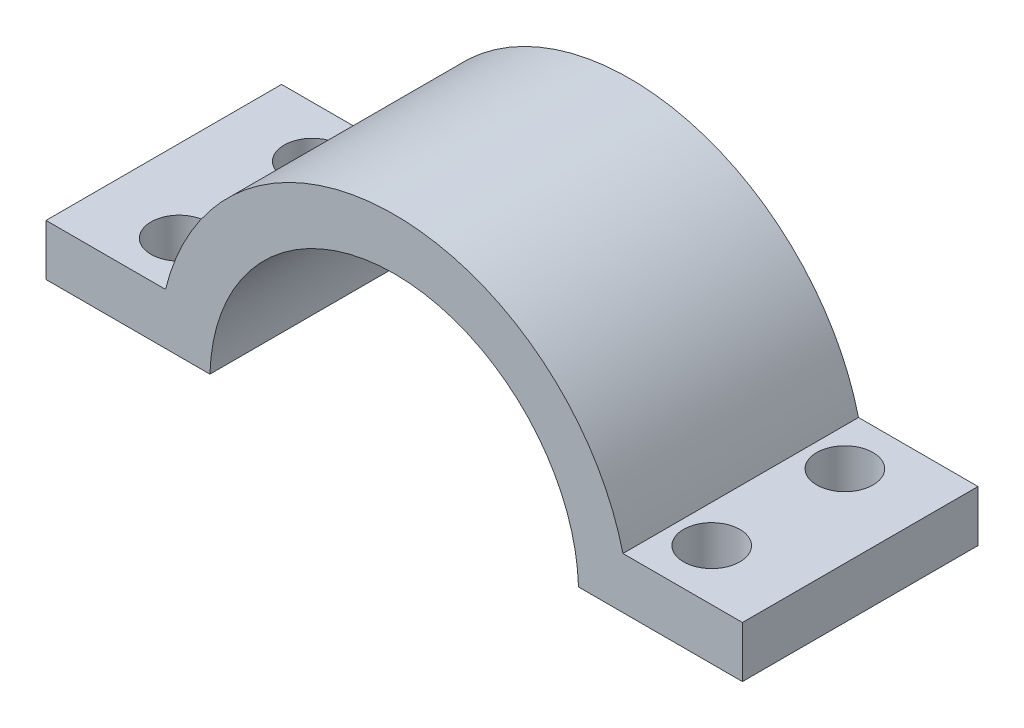
SolidWorks part; units mm, degrees
ref_plane "Front Plane" through (0, 0, 0) normal (0, 0, 1) x (1, 0, 0)
ref_plane "Top Plane" through (0, 0, 0) normal (0, 1, 0) x (1, 0, 0)
ref_plane "Right Plane" through (0, 0, 0) normal (1, 0, 0) x (0, 0, -1)
sketch "Sketch1" plane through (0, 0, 0) normal (0, 0, 1) x (1, 0, 0)
  line L0 (-17.9931, 0.5) -> (-34, 0.5)
  line L1 (-34, 0.5) -> (-34, 5.5)
  line L2 (-34, 5.5) -> (-22.3327, 5.5)
  line L3 (17.9931, 0.5) -> (34, 0.5)
  line L4 (34, 0.5) -> (34, 5.5)
  line L5 (34, 5.5) -> (22.3327, 5.5)
  arc A0 (17.9931, 0.5) -> (-17.9931, 0.5) centre (0, 0) ccw
  arc A1 (22.3327, 5.5) -> (-22.3327, 5.5) centre (0, 0) ccw
  circle A2 centre (0, 0) radius 23 construction
  circle A3 centre (0, 0) radius 18 construction
  point P4 (21.972, 1.1091)
  point P15 (17.9684, 1.0669)
  dimension "D1" = 36
  dimension "D3" = 0.5
  dimension "D4" = 34
  dimension "D5" = 34
  dimension "D6" = 5
  dimension "D7" = 5
  dimension "D2" = 5
extrude "Boss-Extrude1" add sketch "Sketch1" along normal blind 23
sketch "Sketch2" plane through (0, 0.5, 0) normal (0, -1, 0) x (1, 0, 0)
  line L0 (-26, 23) -> (-26, 0) construction
  line L1 (-34, 23) -> (-17.9931, 23) construction
  line L2 (-34, 0) -> (-17.9931, 0) construction
  line L3 (26, 23) -> (26, 0) construction
  line L4 (17.9931, 23) -> (34, 23) construction
  line L5 (17.9931, 0) -> (34, 0) construction
  line L6 (-26, 5) -> (26, 5) construction
  line L7 (-26, 18) -> (26, 18) construction
  circle A0 centre (-26, 18) radius 2.75
  circle A1 centre (-26, 5) radius 2.75
  circle A2 centre (26, 5) radius 2.75
  circle A3 centre (26, 18) radius 2.75
  dimension "D5" = 5.5
  dimension "D6" = 5.5
  dimension "D7" = 5.5
  dimension "D8" = 5.5
  dimension "D1" = 26
  dimension "D2" = 26
  dimension "D3" = 13
  dimension "D4" = 5
extrude "Cut-Extrude1" cut sketch "Sketch2" against normal through all
